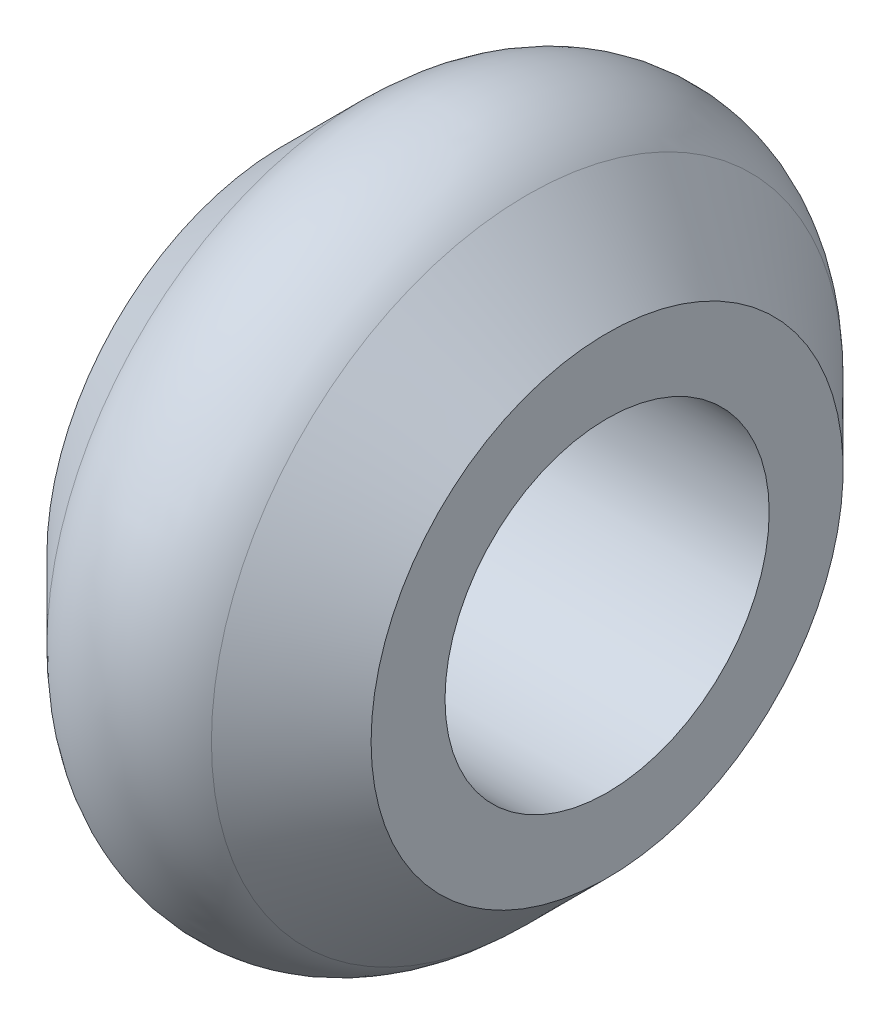
SolidWorks part; units mm, degrees
ref_plane "Front Plane" through (0, 0, 0) normal (0, 0, 1) x (1, 0, 0)
ref_plane "Top Plane" through (0, 0, 0) normal (0, 1, 0) x (1, 0, 0)
ref_plane "Right Plane" through (0, 0, 0) normal (1, 0, 0) x (0, 0, -1)
sketch "Sketch1" plane through (0, 0, 0) normal (0, 0, 1) x (1, 0, 0)
  line L0 (-5.5563, 5.5562) -> (5.5562, 5.5563)
  line L1 (0, 0) -> (0, 5.5562) construction
  line L2 (-5.5563, 5.5562) -> (-5.5563, 8.0899)
  line L3 (-5.5563, 8.0899) -> (0, 13.6461)
  line L4 (5.5563, 8.0899) -> (0, 13.6461)
  line L5 (5.5562, 5.5563) -> (5.5563, 8.0899)
  line L6 (-5.5563, 0) -> (5.5563, 0) construction
  point P7 (0, 0)
  dimension "D1" = 11.1125
  dimension "D2" = 90
  dimension "D3" = 11.1125
  dimension "D4" = 16.1798
revolve "Revolve1" add sketch "Sketch1" angle 360 about L6
fillet "Fillet1" radius 3.9878 1 edges at (0, 0, 13.6461)
